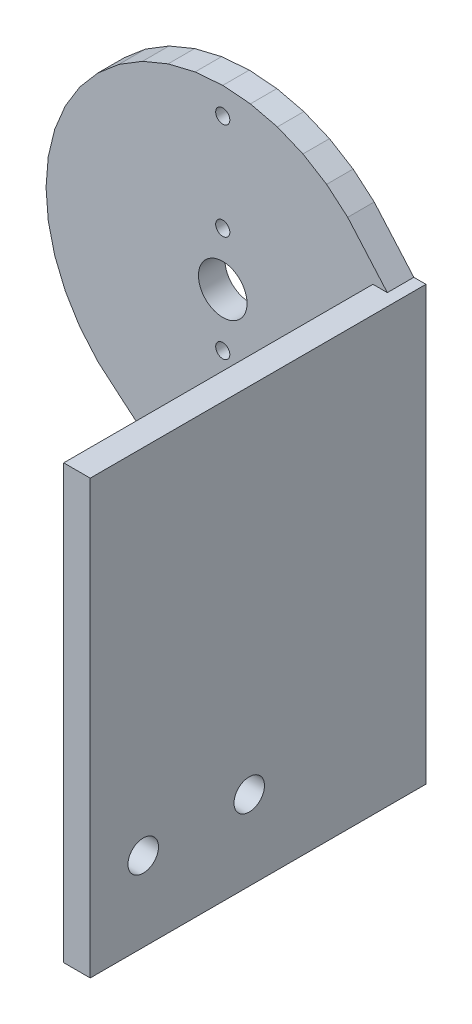
SolidWorks part; units mm, degrees
ref_plane "Front Plane" through (0, 0, 0) normal (0, 0, 1) x (1, 0, 0)
ref_plane "Top Plane" through (0, 0, 0) normal (0, 1, 0) x (1, 0, 0)
ref_plane "Right Plane" through (0, 0, 0) normal (1, 0, 0) x (0, 0, -1)
sketch "Sketch1" plane through (0, 0, 0) normal (0, 0, 1) x (1, 0, 0)
  line L0 (-20, 0) -> (-19.7538, -3.1287)
  line L1 (-19.7538, -3.1287) -> (-19.0211, -6.1803)
  line L2 (-19.0211, -6.1803) -> (-17.8201, -9.0798)
  line L3 (-17.8201, -9.0798) -> (-16.1803, -11.7557)
  line L4 (-16.1803, -11.7557) -> (-14.1421, -14.1421)
  line L5 (-14.1421, -14.1421) -> (-11.7557, -16.1803)
  line L6 (-11.7557, -16.1803) -> (16.0305, -39.5225)
  line L7 (16.0305, -39.5225) -> (16.365, -39.7275)
  line L8 (16.365, -39.7275) -> (16.7275, -39.8776)
  line L9 (16.7275, -39.8776) -> (17.1089, -39.9692)
  line L10 (17.1089, -39.9692) -> (17.5, -40)
  line L11 (17.5, -40) -> (17.8911, -39.9692)
  line L12 (17.8911, -39.9692) -> (18.2725, -39.8776)
  line L13 (18.2725, -39.8776) -> (18.635, -39.7275)
  line L14 (18.635, -39.7275) -> (18.9695, -39.5225)
  line L15 (18.9695, -39.5225) -> (19.2678, -39.2678)
  line L16 (19.2678, -39.2678) -> (19.5225, -38.9695)
  line L17 (19.5225, -38.9695) -> (19.7275, -38.635)
  line L18 (19.7275, -38.635) -> (19.8776, -38.2725)
  line L19 (19.8776, -38.2725) -> (19.9692, -37.8911)
  line L20 (19.9692, -37.8911) -> (20, -37.5)
  line L21 (20, -37.5) -> (20, 6.5)
  line L22 (20, 6.5) -> (19.9692, 6.8911)
  line L23 (19.9692, 6.8911) -> (19.8776, 7.2725)
  line L24 (19.8776, 7.2725) -> (19.7275, 7.635)
  line L25 (19.7275, 7.635) -> (19.5225, 7.9695)
  line L26 (19.5225, 7.9695) -> (19.2678, 8.2678)
  line L27 (19.2678, 8.2678) -> (14.1421, 14.1421)
  line L28 (14.1421, 14.1421) -> (11.7557, 16.1803)
  line L29 (11.7557, 16.1803) -> (9.0798, 17.8201)
  line L30 (9.0798, 17.8201) -> (6.1803, 19.0211)
  line L31 (6.1803, 19.0211) -> (3.1287, 19.7538)
  line L32 (3.1287, 19.7538) -> (0, 20)
  line L33 (0, 20) -> (-3.1287, 19.7538)
  line L34 (-3.1287, 19.7538) -> (-6.1803, 19.0211)
  line L35 (-6.1803, 19.0211) -> (-9.0798, 17.8201)
  line L36 (-9.0798, 17.8201) -> (-11.7557, 16.1803)
  line L37 (-11.7557, 16.1803) -> (-14.1421, 14.1421)
  line L38 (-14.1421, 14.1421) -> (-16.1803, 11.7557)
  line L39 (-16.1803, 11.7557) -> (-17.8201, 9.0798)
  line L40 (-17.8201, 9.0798) -> (-19.0211, 6.1803)
  line L41 (-19.0211, 6.1803) -> (-19.7538, 3.1287)
  line L42 (-19.7538, 3.1287) -> (-20, 0)
extrude "Boss-Extrude1" add sketch "Sketch1" along normal blind 3 from offset 26
sketch "Sketch2" plane through (0, 0, 0) normal (0, 0, 1) x (1, 0, 0)
  line L0 (17, -40) -> (20, -40)
  line L1 (20, -40) -> (20, 9)
  line L2 (20, 9) -> (17, 9)
  line L3 (17, 9) -> (17, -40)
extrude "Boss-Extrude2" add sketch "Sketch2" along normal blind 38 from offset 26
sketch "Sketch3" plane through (0, 0, 0) normal (0, 0, 1) x (1, 0, 0)
  circle A0 centre (0, 0) radius 2.75
  circle A1 centre (0, 6) radius 0.8
  circle A2 centre (0, -6) radius 0.8
  circle A3 centre (0, 17) radius 0.8
  circle A4 centre (0, -17) radius 0.8
extrude "Cut-Extrude1" cut sketch "Sketch3" against normal through all and the other way through all
sketch "Sketch4" plane through (0, 0, 0) normal (1, 0, 0) x (0, 0, -1)
  circle A0 centre (-6, -31) radius 1.725
  circle A1 centre (6, -31) radius 1.725
extrude "Cut-Extrude2" cut sketch "Sketch4" against normal through all and the other way through all
